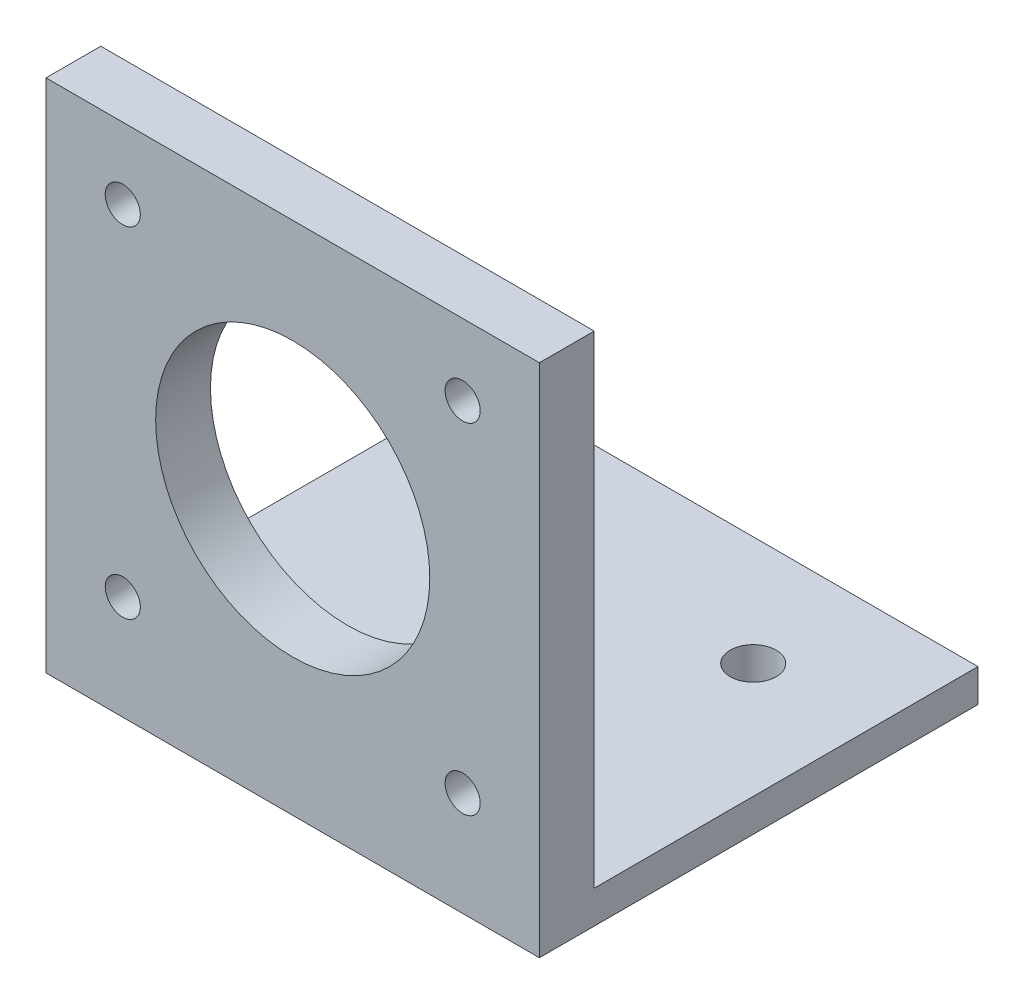
SolidWorks part; units mm, degrees
ref_plane "正面" through (0, 0, 0) normal (0, 0, 1) x (1, 0, 0)
ref_plane "平面" through (0, 0, 0) normal (0, 1, 0) x (1, 0, 0)
ref_plane "右側面" through (0, 0, 0) normal (1, 0, 0) x (0, 0, -1)
sketch "ｽｹｯﾁ2" plane through (0, 0, 0) normal (0, 1, 0) x (1, 0, 0)
  line L1 (-22.5, -20) -> (22.5, -20)
  line L2 (-22.5, -20) -> (-22.5, 20)
  line L3 (-22.5, 20) -> (22.5, 20)
  line L4 (22.5, -20) -> (22.5, 20)
  line L5 (-22.5, -20) -> (22.5, 20) construction
  line L6 (-22.5, 20) -> (22.5, -20) construction
  point P0 (0, 0)
  dimension "D1" = 45
  dimension "D2" = 40
extrude "ﾎﾞｽ - 押し出し1" add sketch "ｽｹｯﾁ2" along normal blind 3
sketch "ｽｹｯﾁ3" plane through (0, 3, 0) normal (0, 1, 0) x (1, 0, 0)
  line L0 (0, 20) -> (0, -20) construction
  line L1 (22.5, 20) -> (-22.5, 20) construction
  line L2 (-22.5, -20) -> (22.5, -20) construction
  line L3 (-22.5, 0) -> (22.5, 0) construction
  line L4 (-22.5, 20) -> (-22.5, -20) construction
  line L5 (22.5, -20) -> (22.5, 20) construction
  circle A0 centre (-12, 10) radius 2.1
  circle A4 centre (12, 10) radius 2.1
  circle A5 centre (12, -10) radius 2.1
  circle A6 centre (-12, -10) radius 2.1
  dimension "D1" = 4.2
  dimension "D3" = 10
  dimension "D2" = 12
extrude "ｶｯﾄ - 押し出し1" cut sketch "ｽｹｯﾁ3" against normal through all
sketch "ｽｹｯﾁ4" plane through (0, 3, 0) normal (0, 1, 0) x (1, 0, 0)
  line L0 (22.5, -20) -> (22.5, 20) construction
  line L1 (-22.5, -20) -> (22.5, -20)
  line L2 (-22.5, -20) -> (-22.5, -15)
  line L3 (-22.5, -15) -> (22.5, -15)
  line L4 (22.5, -20) -> (22.5, -15)
  dimension "D1" = 5
extrude "ﾎﾞｽ - 押し出し2" add sketch "ｽｹｯﾁ4" along normal blind 44 contours L3 L4 L1 L2
sketch "ｽｹｯﾁ6" plane through (0, 0, 15) normal (0, 0, -1) x (-1, 0, 0)
  line L0 (0, 47) -> (0, 3) construction
  line L1 (22.5, 47) -> (-22.5, 47) construction
  line L2 (-22.5, 3) -> (22.5, 3) construction
  line L3 (-22.5, 25) -> (22.5, 25) construction
  line L4 (-22.5, 47) -> (-22.5, 3) construction
  line L5 (22.5, 47) -> (22.5, 3) construction
  circle A0 centre (-15.5, 40.5) radius 1.6
  circle A1 centre (15.5, 40.5) radius 1.6
  circle A2 centre (15.5, 9.5) radius 1.6
  circle A3 centre (-15.5, 9.5) radius 1.6
  circle A4 centre (0, 25) radius 12.5
  dimension "D1" = 3.2
  dimension "D2" = 31
  dimension "D3" = 31
  dimension "D4" = 25
extrude "ｶｯﾄ - 押し出し3" cut sketch "ｽｹｯﾁ6" against normal through all
